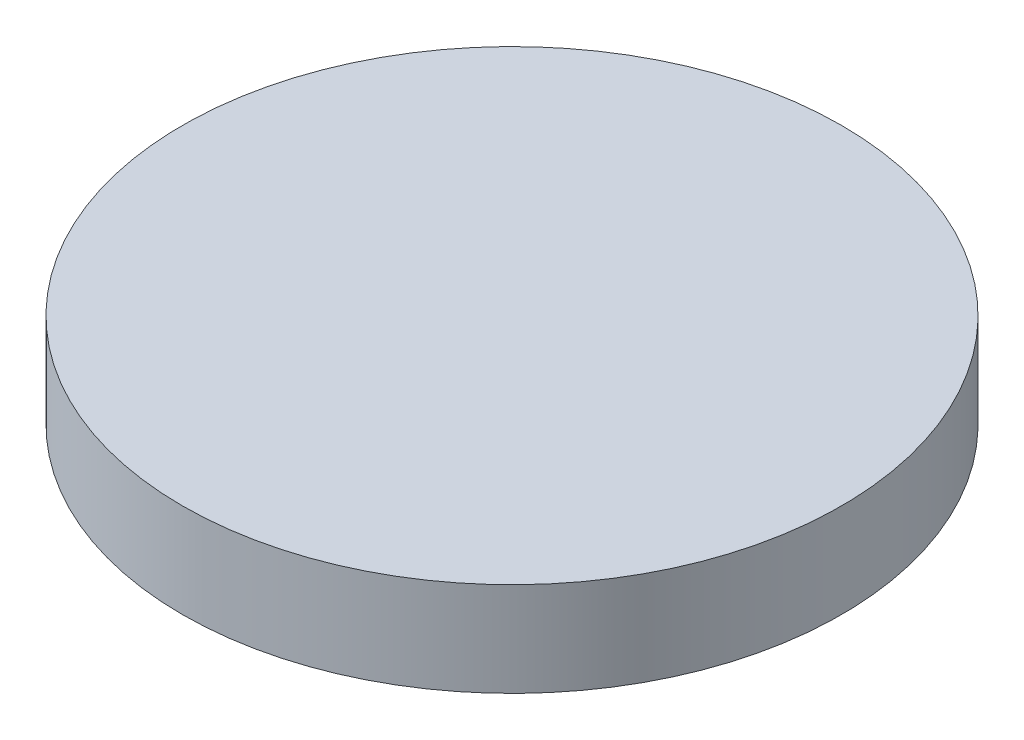
SolidWorks part; units mm, degrees
material "cardboard"
ref_plane "Front Plane" through (0, 0, 0) normal (0, 0, 1) x (1, 0, 0)
ref_plane "Top Plane" through (0, 0, 0) normal (0, 1, 0) x (1, 0, 0)
ref_plane "Right Plane" through (0, 0, 0) normal (1, 0, 0) x (0, 0, -1)
sketch "Sketch1" plane through (0, 0, 0) normal (0, 1, 0) x (1, 0, 0)
  circle A0 centre (0, 0) radius 70
  dimension "D1" = 140
extrude "Boss-Extrude1" add sketch "Sketch1" along normal blind 20
